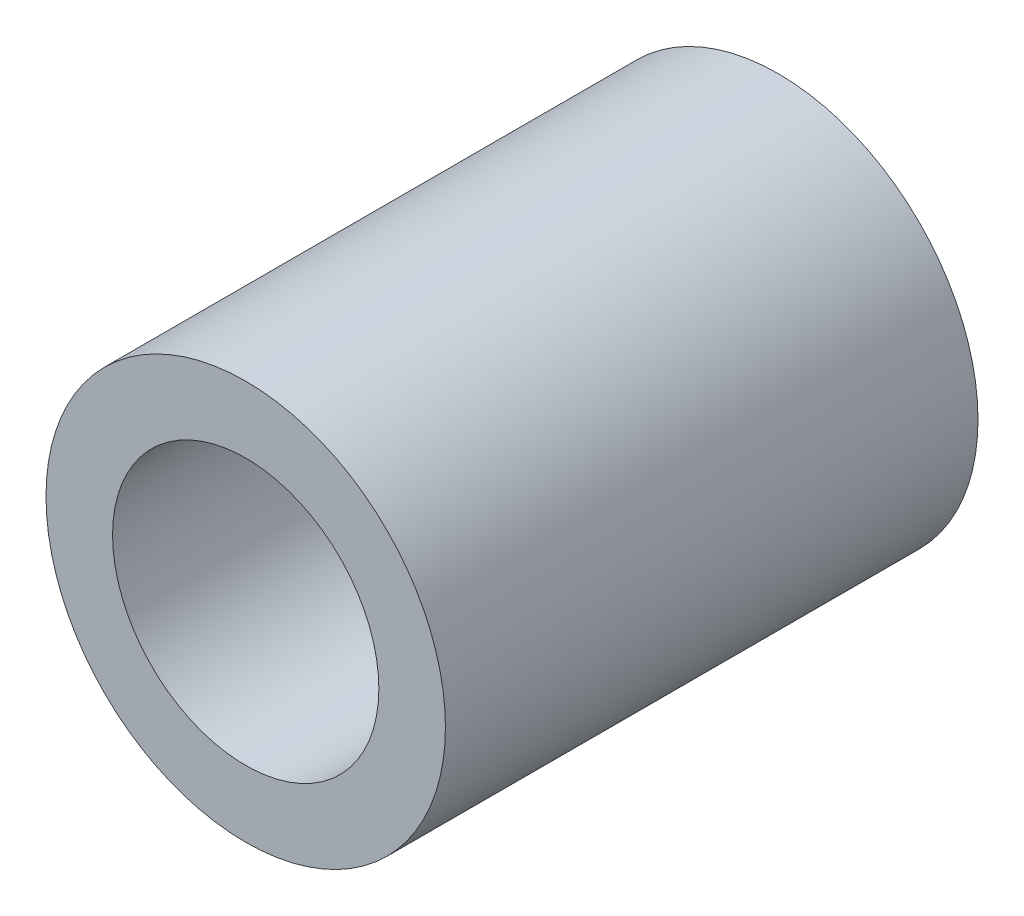
SolidWorks part; units mm, degrees
ref_plane "Front Plane" through (0, 0, 0) normal (0, 0, 1) x (1, 0, 0)
ref_plane "Top Plane" through (0, 0, 0) normal (0, 1, 0) x (1, 0, 0)
ref_plane "Right Plane" through (0, 0, 0) normal (1, 0, 0) x (0, 0, -1)
sketch "Sketch1" plane through (0, 0, 0) normal (0, 0, 1) x (1, 0, 0)
  circle A0 centre (0, 0) radius 4.7625
  circle A1 centre (0, 0) radius 3.175
  dimension "D1" = 9.525
  dimension "ID" = 6.35
extrude "Extrude1" add sketch "Sketch1" along normal mid plane 12.7
sketch "Sketch2" plane through (0, 0, 0) normal (1, 0, 0) x (0, 0, -1)
  line L0 (-6.35, -3.175) -> (6.35, -3.175) construction
  line L3 (6.35, 3.175) -> (-6.35, 3.175) construction
  line L5 (-6.35, -3.175) -> (6.35, -3.175)
  line L6 (6.35, 3.175) -> (-6.35, 3.175)
sketch "Sketch4" plane through (0, 0, 6.35) normal (0, 0, 1) x (1, 0, 0)
  line L0 (0, 0) -> (-2.2451, 2.2451)
  line L1 (0, -24.4475) -> (0, 24.4475) construction
  circle A0 centre (0, 0) radius 3.175 construction
  dimension "D1" = 45
